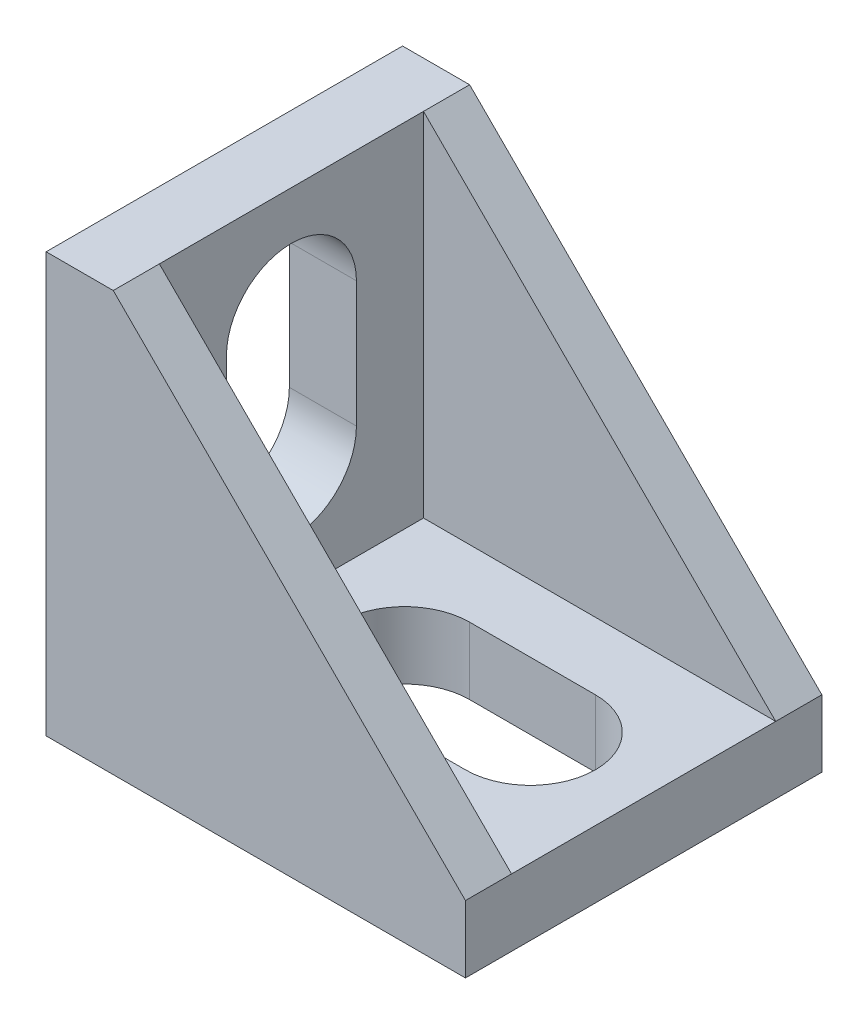
SolidWorks part; units mm, degrees
ref_plane "前视基准面" through (0, 0, 0) normal (0, 0, 1) x (1, 0, 0)
ref_plane "上视基准面" through (0, 0, 0) normal (0, 1, 0) x (1, 0, 0)
ref_plane "右视基准面" through (0, 0, 0) normal (1, 0, 0) x (0, 0, -1)
sketch "草图1" plane through (0, 0, 0) normal (0, 0, 1) x (1, 0, 0)
  line L0 (0, 0) -> (20, 0)
  line L1 (0, 0) -> (0, 20)
  line L2 (0, 20) -> (3.2, 20)
  line L3 (20, 0) -> (20, 3.2)
  line L4 (3.2, 20) -> (20, 3.2)
extrude "凸台-拉伸1" add sketch "草图1" along normal blind 17
sketch "草图2" plane through (0, 20, 0) normal (0, 1, 0) x (1, 0, 0)
  line L0 (3.2, -2.2) -> (3.2, -14.8)
  line L1 (3.2, -17) -> (3.2, 0) construction
  line L3 (3.2, -2.2) -> (23.0942, -2.2)
  line L4 (23.0942, -2.2) -> (23.0942, -14.8)
  line L5 (23.0942, -14.8) -> (3.2, -14.8)
extrude "切除-拉伸1" cut sketch "草图2" against normal blind 16.8
sketch "草图3" plane through (0, 3.2, 0) normal (0, 1, 0) x (1, 0, 0)
  line L5 (8.6, -5.4) -> (14.6, -5.4)
  line L7 (14.6, -11.6) -> (8.6, -11.6)
  arc A1 (8.6, -5.4) -> (8.6, -11.6) centre (8.6, -8.5) ccw
  arc A3 (14.6, -11.6) -> (14.6, -5.4) centre (14.6, -8.5) ccw
extrude "切除-拉伸2" cut sketch "草图3" against normal blind 16.8
sketch "草图4" plane through (3.2, 0, 0) normal (1, 0, 0) x (0, 0, -1)
  line L5 (-5.4, 14.6) -> (-5.4, 8.6)
  line L7 (-11.6, 8.6) -> (-11.6, 14.6)
  arc A1 (-5.4, 14.6) -> (-11.6, 14.6) centre (-8.5, 14.6) ccw
  arc A2 (-11.6, 8.6) -> (-5.4, 8.6) centre (-8.5, 8.6) ccw
extrude "切除-拉伸3" cut sketch "草图4" against normal blind 16.8
